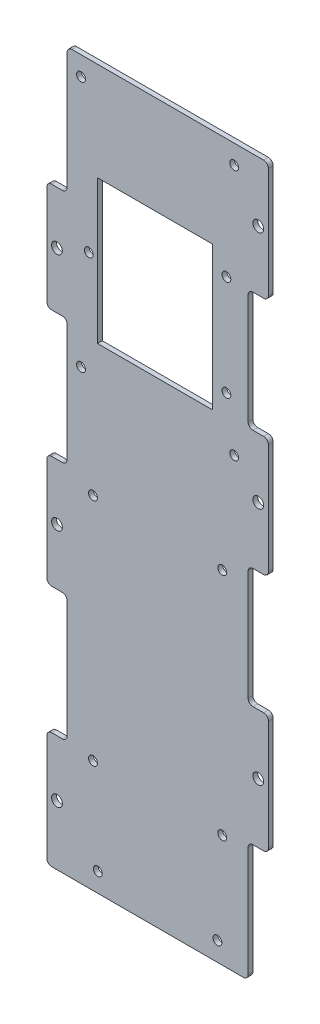
SolidWorks part; units mm, degrees
material "Acrylic (Medium-high impact)"
ref_plane "Front Plane" through (0, 0, 0) normal (0, 0, 1) x (1, 0, 0)
ref_plane "Top Plane" through (0, 0, 0) normal (0, 1, 0) x (1, 0, 0)
ref_plane "Right Plane" through (0, 0, 0) normal (1, 0, 0) x (0, 0, -1)
sketch "Sketch1" plane through (0, 0, 0) normal (0, 0, 1) x (1, 0, 0)
  line L1 (46.3, -150) -> (-46.3, -150)
  line L2 (46.3, -150) -> (46.3, 150)
  line L3 (46.3, 150) -> (-46.3, 150)
  line L4 (-46.3, -150) -> (-46.3, 150)
  line L5 (46.3, -150) -> (-46.3, 150) construction
  line L6 (46.3, 150) -> (-46.3, -150) construction
  point P0 (0, 0)
  dimension "D1" = 92.6
  dimension "D2" = 300
extrude "Boss-Extrude1" add sketch "Sketch1" along normal blind 2
sketch "Sketch2" plane through (0, 0, 0) normal (0, 0, 1) x (1, 0, 0)
  line L0 (-42.06, 150) -> (-42.06, -150) construction
  line L1 (46.3, 150) -> (-46.3, 150) construction
  line L2 (-46.3, -150) -> (46.3, -150) construction
  line L3 (42.06, 150) -> (42.06, -150) construction
  line L5 (-37.82, 97) -> (-46.3, 97)
  line L6 (-37.82, 97) -> (-37.82, 150)
  line L7 (-37.82, 150) -> (-46.3, 150)
  line L8 (-46.3, 97) -> (-46.3, 150)
  line L9 (-37.82, 97) -> (-46.3, 150) construction
  line L10 (-37.82, 150) -> (-46.3, 97) construction
  line L18 (46.3, -150) -> (46.3, 150) construction
  line L23 (37.82, 100) -> (46.3, 100)
  line L24 (37.82, 100) -> (37.82, 50)
  line L25 (37.82, 50) -> (46.3, 50)
  line L26 (46.3, 100) -> (46.3, 50)
  line L27 (37.82, 100) -> (46.3, 50) construction
  line L28 (37.82, 50) -> (46.3, 100) construction
  line L29 (46.3, -50) -> (37.82, -50)
  line L30 (46.3, -50) -> (46.3, 0)
  line L31 (46.3, 0) -> (37.82, 0)
  line L32 (37.82, -50) -> (37.82, 0)
  line L33 (46.3, -50) -> (37.82, 0) construction
  line L34 (46.3, 0) -> (37.82, -50) construction
  line L35 (-37.82, -1.5) -> (-46.3, -1.5)
  line L36 (-37.82, -1.5) -> (-37.82, 51.5)
  line L37 (-37.82, 51.5) -> (-46.3, 51.5)
  line L38 (-46.3, -1.5) -> (-46.3, 51.5)
  line L39 (-37.82, -1.5) -> (-46.3, 51.5) construction
  line L40 (-37.82, 51.5) -> (-46.3, -1.5) construction
  line L41 (-37.82, -101.5) -> (-46.3, -101.5)
  line L42 (-37.82, -101.5) -> (-37.82, -48.5)
  line L43 (-37.82, -48.5) -> (-46.3, -48.5)
  line L44 (-46.3, -101.5) -> (-46.3, -48.5)
  line L45 (-37.82, -101.5) -> (-46.3, -48.5) construction
  line L46 (-37.82, -48.5) -> (-46.3, -101.5) construction
  line L47 (37.82, -150) -> (46.3, -150)
  line L48 (37.82, -150) -> (37.82, -100)
  line L49 (37.82, -100) -> (46.3, -100)
  line L50 (46.3, -150) -> (46.3, -100)
  line L51 (37.82, -150) -> (46.3, -100) construction
  line L52 (37.82, -100) -> (46.3, -150) construction
  line L54 (42.06, 50) -> (-134.3061, 50) construction
  circle A0 centre (-42.06, 75) radius 2.25
  circle A1 centre (42.06, 125) radius 2.25
  circle A6 centre (42.06, 25) radius 2.25
  circle A7 centre (42.06, -75) radius 2.25
  circle A8 centre (-42.06, -25) radius 2.25
  circle A9 centre (-42.06, -125) radius 2.25
  point P12 (-42.06, 123.5)
  point P14 (-42.06, 25)
  point P24 (42.06, 75)
  point P29 (-42.06, -75)
  point P37 (42.06, -25)
  point P45 (42.06, -125)
  dimension "D1" = 4.5
  dimension "D2" = 4.5
  dimension "D19" = 75
  dimension "D20" = 4.5
  dimension "D22" = 4.5
  dimension "D25" = 4.5
  dimension "D29" = 4.5
  dimension "D4" = 75
  dimension "D5" = 25
  dimension "D6" = 84.12
  dimension "D7" = 42.06
  dimension "D9" = 8.48
  dimension "D10" = 53
  dimension "D11" = 26.5
  dimension "D3" = 53
  dimension "D13" = 8.48
  dimension "D14" = 8.48
  dimension "D15" = 50
  dimension "D16" = 100
  dimension "D17" = 50
  dimension "D18" = 100
  dimension "D8" = 8.48
  dimension "D21" = 25
  dimension "D23" = 175
  dimension "D24" = 125
  dimension "D12" = 53
  dimension "D26" = 100
  dimension "D27" = 50
  dimension "D28" = 25
  dimension "D30" = 25
  dimension "D31" = 8.48
extrude "Cut-Extrude5" cut sketch "Sketch2" along normal blind 10
fillet "Fillet3" radius 2 24 edges at (-46.3, 97, 1) (-37.82, 97, 1) (-37.82, 150, 1) (46.3, 150, 1) (46.3, 100, 1) (37.82, 100, 1) (37.82, 50, 1) (46.3, 50, 1) (46.3, 0, 1) (37.82, 0, 1) (37.82, -50, 1) (46.3, -50, 1) (46.3, -100, 1) (37.82, -100, 1) (37.82, -150, 1) (-46.3, -150, 1) (-46.3, -101.5, 1) (-37.82, -101.5, 1) (-37.82, -48.5, 1) (-46.3, -48.5, 1) (-46.3, -1.5, 1) (-37.82, -1.5, 1) (-37.82, 51.5, 1) (-46.3, 51.5, 1)
sketch "Sketch4" plane through (0, 0, 0) normal (0, 0, -1) x (-1, 0, 0)
  circle A0 centre (-25, -142) radius 1.85
  circle A1 centre (25, -142) radius 1.85
  circle A2 centre (32, 142) radius 1.85
  circle A3 centre (-32, 142) radius 1.85
  dimension "D1" = 3.7
extrude "Cut-Extrude6" cut sketch "Sketch4" against normal blind 10
sketch "Sketch5" plane through (0, 0, 0) normal (0, 0, -1) x (-1, 0, 0)
  circle A0 centre (-27, -103) radius 1.85
  circle A1 centre (27, -103) radius 1.85
  circle A2 centre (-27, -7) radius 1.85
  circle A3 centre (27, -7) radius 1.85
  circle A4 centre (-32, 37) radius 1.85
  circle A5 centre (32, 37) radius 1.85
  circle A6 centre (-28.75, 58) radius 1.85
  circle A7 centre (28.75, 80.08) radius 1.85
  circle A8 centre (-28.75, 100) radius 1.85
  dimension "D1" = 3.7
extrude "Cut-Extrude7" cut sketch "Sketch5" against normal blind 5
sketch "Sketch6" plane through (0, 0, 0) normal (0, 0, -1) x (-1, 0, 0)
  line L0 (1.1, 103.6107) -> (1.1, 116.3154) construction
  line L1 (-22.9, 108.9233) -> (25.1, 108.9233)
  line L2 (-22.9, 108.9233) -> (-22.9, 48.9233)
  line L3 (-22.9, 48.9233) -> (25.1, 48.9233)
  line L4 (25.1, 108.9233) -> (25.1, 48.9233)
  line L5 (17.1, 103.6107) -> (-14.9, 103.6107) construction
  point P8 (1.1, 108.9233)
  dimension "D1" = 48
  dimension "D2" = 60
extrude "Cut-Extrude8" cut sketch "Sketch6" against normal blind 10
